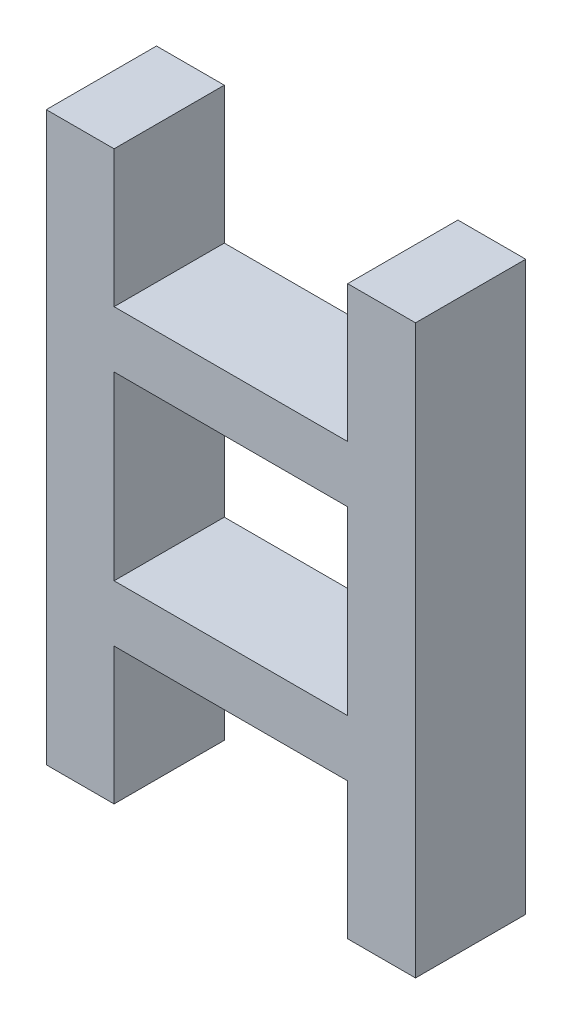
SolidWorks part; units mm, degrees
ref_plane "Front Plane" through (0, 0, 0) normal (0, 0, 1) x (1, 0, 0)
ref_plane "Top Plane" through (0, 0, 0) normal (0, 1, 0) x (1, 0, 0)
ref_plane "Right Plane" through (0, 0, 0) normal (1, 0, 0) x (0, 0, -1)
sketch "Sketch1" plane through (0, 0, 0) normal (0, 0, 1) x (1, 0, 0)
  line L0 (1247.2096, 948.8272) -> (1247.2096, 941.568)
  line L1 (1247.2096, 941.568) -> (1243.6096, 941.568)
  line L2 (1243.6096, 941.568) -> (1243.6096, 971.6864)
  line L3 (1263.2096, 971.6864) -> (1263.2096, 941.568)
  line L4 (1243.6096, 971.6864) -> (1247.2096, 971.6864)
  line L5 (1247.2096, 971.6864) -> (1247.2096, 964.4272)
  line L6 (1259.6096, 941.568) -> (1259.6096, 948.8272)
  line L7 (1259.6096, 971.6864) -> (1263.2096, 971.6864)
  line L8 (1259.6096, 964.4272) -> (1259.6096, 971.6864)
  line L9 (1247.2096, 964.4272) -> (1259.6096, 964.4272)
  line L11 (1247.2096, 948.8272) -> (1259.6096, 948.8272)
  line L16 (1247.2096, 961.4272) -> (1259.6096, 961.4272)
  line L17 (1247.2096, 961.4272) -> (1247.2096, 951.8272)
  line L18 (1247.2096, 951.8272) -> (1259.6096, 951.8272)
  line L19 (1253.4096, -38.8351) -> (1253.4096, 49961.1649) construction
  line L25 (1259.6096, 961.4272) -> (1259.6096, 951.8272)
  line L26 (1253.4096, 962.9691) -> (1243.6096, 962.9691) construction
  line L28 (1259.6096, 941.568) -> (1263.2096, 941.568)
  point P28 (1253.4096, 964.4272)
  point P30 (1253.4096, 961.4272)
  dimension "D1" = 12.4
  dimension "D2" = 7.2592
  dimension "D3" = 3.6
  dimension "D4" = 3.6
  dimension "D5" = 3
  dimension "D6" = 15.6
  dimension "D7" = 3
extrude "Boss-Extrude1" add sketch "Sketch1" along normal blind 5.85
